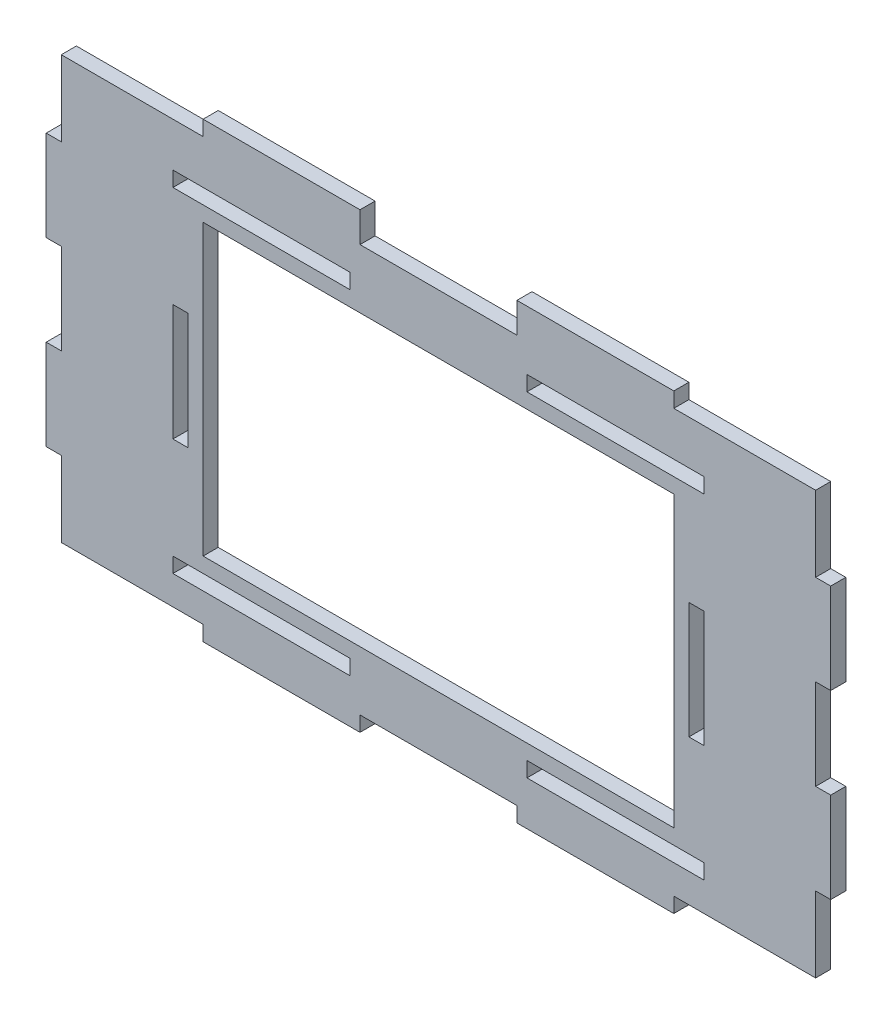
SolidWorks part; units mm, degrees
ref_plane "Alzado" through (0, 0, 0) normal (0, 0, 1) x (1, 0, 0)
ref_plane "Planta" through (0, 0, 0) normal (0, 1, 0) x (1, 0, 0)
ref_plane "Vista lateral" through (0, 0, 0) normal (1, 0, 0) x (0, 0, -1)
sketch "Croquis1" plane through (0, 0, 0) normal (0, 0, 1) x (1, 0, 0)
  line L0 (130, 150) -> (130, 129.9372) construction
  line L1 (52, 0) -> (104, 0)
  line L2 (0, 30) -> (0, 60)
  line L3 (52, 150) -> (104, 150)
  line L4 (260, 30) -> (260, 60)
  line L5 (0, 75) -> (16.5526, 75) construction
  line L6 (0, 120) -> (5, 120)
  line L7 (0, 90) -> (0, 120)
  line L8 (5, 90) -> (0, 90)
  line L9 (0, 30) -> (5, 30)
  line L10 (0, 0) -> (5, 0) construction
  line L11 (5, 60) -> (0, 60)
  line L12 (5, 30) -> (5, 5)
  line L13 (5, 60) -> (5, 90)
  line L14 (5, 120) -> (5, 145)
  line L15 (0, 30) -> (0, 0) construction
  line L16 (255, 30) -> (255, 5)
  line L17 (260, 30) -> (255, 30)
  line L18 (255, 60) -> (260, 60)
  line L19 (255, 60) -> (255, 90)
  line L20 (255, 90) -> (260, 90)
  line L21 (260, 120) -> (255, 120)
  line L22 (255, 120) -> (255, 145)
  line L23 (260, 90) -> (260, 120)
  line L24 (52, 150) -> (52, 145)
  line L25 (208, 5) -> (255, 5)
  line L26 (104, 145) -> (104, 150)
  line L27 (208, 150) -> (208, 145)
  line L28 (156, 145) -> (156, 150)
  line L29 (208, 0) -> (208, 5)
  line L30 (52, 145) -> (5, 145)
  line L31 (104, 145) -> (156, 145)
  line L32 (208, 145) -> (255, 145)
  line L33 (156, 150) -> (208, 150)
  line L34 (156, 5) -> (156, 0)
  line L35 (104, 5) -> (156, 5)
  line L36 (104, 5) -> (104, 0)
  line L37 (52, 0) -> (52, 5)
  line L38 (52, 5) -> (5, 5)
  line L39 (156, 0) -> (208, 0)
  line L40 (0, 0) -> (52, 0) construction
  dimension "D1" = 5
  dimension "D2" = 260
  dimension "D3" = 5
  dimension "D4" = 30
  dimension "D5" = 30
  dimension "D6" = 52
  dimension "D7" = 52
  dimension "D8" = 5
  dimension "D9" = 150
  dimension "D10" = 52
  dimension "D11" = 25
extrude "Saliente-Extruir1" add sketch "Croquis1" along normal blind 5
sketch "Croquis2" plane through (0, 0, 5) normal (0, 0, 1) x (1, 0, 0)
  line L0 (156, 150) -> (156, 145) construction
  line L1 (104, 145) -> (156, 145)
  line L2 (104, 145) -> (104, 140)
  line L3 (104, 140) -> (156, 140)
  line L4 (156, 145) -> (156, 140)
  dimension "D1" = 5
extrude "Cortar-Extruir1" cut sketch "Croquis2" against normal blind 10
sketch "Croquis3" plane through (0, 0, 5) normal (0, 0, 1) x (1, 0, 0)
  line L0 (47, 91.8) -> (47, 53.2)
  line L1 (52, 120.4) -> (208, 120.4)
  line L2 (52, 120.4) -> (52, 24.6)
  line L3 (52, 24.6) -> (208, 24.6)
  line L4 (208, 120.4) -> (208, 24.6)
  line L5 (255, 60) -> (255, 90) construction
  line L6 (104, 140) -> (156, 140) construction
  line L7 (47, 19.6) -> (100.6667, 19.6)
  line L8 (213, 91.8) -> (213, 53.2)
  line L9 (47, 125.4) -> (100.6667, 125.4)
  line L10 (42, 130.4) -> (42, 125.4)
  line L11 (42, 14.6) -> (100.6667, 14.6)
  line L12 (218, 130.4) -> (218, 125.4)
  line L13 (42, 130.4) -> (100.6667, 130.4)
  line L14 (100.6667, 130.4) -> (100.6667, 125.4)
  line L15 (130, 125.4) -> (130, 109.9365) construction
  line L16 (42, 91.8) -> (47, 91.8)
  line L17 (52, 72.5) -> (67.2306, 72.5) construction
  line L18 (100.6667, 14.6) -> (100.6667, 19.6)
  line L19 (42, 53.2) -> (47, 53.2)
  line L20 (159.3333, 14.6) -> (159.3333, 19.6)
  line L21 (218, 53.2) -> (213, 53.2)
  line L22 (218, 91.8) -> (213, 91.8)
  line L23 (159.3333, 130.4) -> (159.3333, 125.4)
  line L24 (47, 125.4) -> (42, 125.4)
  line L25 (213, 125.4) -> (218, 125.4)
  line L26 (213, 19.6) -> (218, 19.6)
  line L27 (47, 19.6) -> (42, 19.6)
  line L28 (42, 19.6) -> (42, 14.6)
  line L29 (42, 130.4) -> (42, 14.6) construction
  line L30 (47, 125.4) -> (47, 19.6) construction
  line L31 (42, 91.8) -> (42, 53.2)
  line L32 (159.3333, 14.6) -> (218, 14.6)
  line L33 (42, 14.6) -> (218, 14.6) construction
  line L34 (159.3333, 19.6) -> (213, 19.6)
  line L35 (47, 19.6) -> (213, 19.6) construction
  line L36 (218, 19.6) -> (218, 14.6)
  line L37 (218, 130.4) -> (218, 14.6) construction
  line L38 (213, 125.4) -> (213, 19.6) construction
  line L39 (218, 91.8) -> (218, 53.2)
  line L40 (159.3333, 130.4) -> (218, 130.4)
  line L41 (42, 130.4) -> (218, 130.4) construction
  line L42 (159.3333, 125.4) -> (213, 125.4)
  line L43 (47, 125.4) -> (213, 125.4) construction
  dimension "D1" = 156
  dimension "D2" = 95.8
  dimension "D3" = 47
  dimension "D4" = 19.6
  dimension "D5" = 5
  dimension "D7" = 58.6667
  dimension "D8" = 38.6
  dimension "D6" = 5
extrude "Cortar-Extruir2" cut sketch "Croquis3" against normal blind 10
